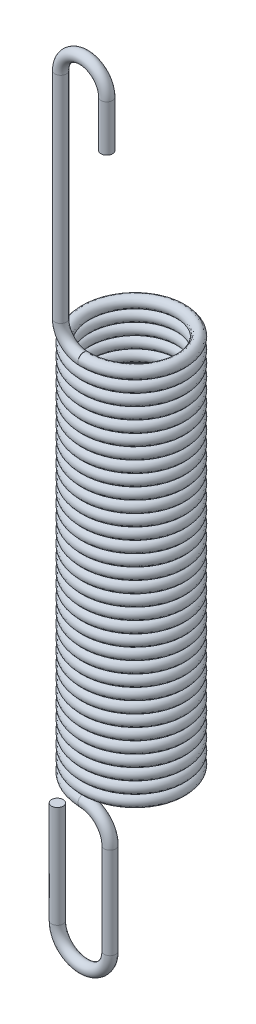
SolidWorks part; units mm, degrees
ref_plane "Front Plane" through (0, 0, 0) normal (0, 0, 1) x (1, 0, 0)
ref_plane "Top Plane" through (0, 0, 0) normal (0, 1, 0) x (1, 0, 0)
ref_plane "Right Plane" through (0, 0, 0) normal (1, 0, 0) x (0, 0, -1)
sketch "Sketch2" plane through (0, 0, 0) normal (0, 1, 0) x (1, 0, 0)
  circle A0 centre (0, 0) radius 19.6
curve "Helix/Spiral1" pitch 4.7664 height 157.29 turns 33
ref_plane "Plane1" through (0, 0, 19.6) normal (0, 0, 1) x (1, 0, 0)
sketch "Sketch3" plane through (0, 0, 19.6) normal (0, 0, 1) x (1, 0, 0)
  line L0 (10.85, -10.85) -> (10.85, -48.5)
  line L1 (-10.85, -48.5) -> (-10.85, -6.5)
  arc A0 (0, 0) -> (10.85, -10.85) centre (0, -10.85) cw
  arc A1 (10.85, -48.5) -> (-10.85, -48.5) centre (0, -48.5) cw
sketch "Sketch5" plane through (0, 0, 19.6) normal (0, 0, 1) x (1, 0, 0)
  line L0 (-9.5, 166.79) -> (-9.5, 255.29)
  line L1 (9.5, 255.29) -> (9.5, 236.29)
  arc A0 (0, 157.29) -> (-9.5, 166.79) centre (0, 166.79) cw
  arc A1 (-9.5, 255.29) -> (9.5, 255.29) centre (0, 255.29) cw
  spline S0 degree 3 poles (0, 0) (-2.088, 0.0808) (-6.2947, 0.2436) (-11.9376, 0.4869) (-16.3676, 0.7305) (-19.1242, 0.9739) (-19.9279, 1.2174) (-18.6961, 1.4609) (-15.5547, 1.7044) (-10.8245, 1.9479) (-4.9888, 2.1913) (1.3565, 2.4348) (7.5632, 2.6783) (12.9975, 2.9218) (17.1042, 3.1653) (19.4639, 3.4088) (19.8355, 3.6522) (18.1812, 3.8957) (14.6699, 4.1392) (9.6602, 4.3827) (3.6639, 4.6262) (-2.7067, 4.8697) (-8.8009, 5.1131) (-13.9961, 5.3566) (-17.7618, 5.6001) (-19.7133, 5.8436) (-19.6513, 6.0871) (-17.5822, 6.3306) (-13.7172, 6.574) (-8.4512, 6.8175) (-2.322, 7.061) (4.0444, 7.3045) (9.9977, 7.548) (14.9298, 7.7915) (18.337, 8.0349) (19.8713, 8.2784) (19.376, 8.5219) (16.9016, 8.7654) (12.7009, 9.0089) (7.203, 9.2524) (0.9693, 9.4958) (-5.3634, 9.7393) (-11.1482, 9.9828) (-15.7944, 10.2263) (-18.8273, 10.4698) (-19.9373, 10.7133) (-19.0109, 10.9567) (-16.1427, 11.2002) (-11.6258, 11.4437) (-5.9214, 11.6872) (0.3878, 11.9307) (6.6574, 12.1741) (12.2471, 12.4176) (16.5858, 12.6611) (19.2304, 12.9046) (19.9109, 13.1481) (18.5577, 13.3916) (15.3091, 13.635) (10.4968, 13.8785) (4.6123, 14.122) (-1.7432, 14.3655) (-7.9207, 14.609) (-13.2892, 14.8525) (-17.3003, 15.0959) (-19.5444, 15.3394) (-19.7922, 15.5829) (-18.0185, 15.8264) (-14.4045, 16.0699) (-9.3191, 16.3134) (-3.2819, 16.5568) (3.0905, 16.8003) (9.1472, 17.0438) (14.2697, 17.2873) (17.9346, 17.5308) (19.7678, 17.7743) (19.5819, 18.0177) (17.3959, 18.2612) (13.4331, 18.5047) (8.0983, 18.7482) (1.9363, 18.9917) (-4.4234, 19.2352) (-10.3314, 19.4786) (-15.1841, 19.7221) (-18.4859, 19.9656) (-19.8996, 20.2091) (-19.2808, 20.4526) (-16.6926, 20.6961) (-12.3995, 20.9395) (-6.8399, 21.183) (-0.5817, 21.4265) (5.7359, 21.67) (11.4677, 21.9135) (16.0281, 22.157) (18.9515, 22.4004) (19.9392, 22.6439) (18.8903, 22.8874) (15.912, 23.1309) (11.3085, 23.3744) (5.5499, 23.6178) (-0.7756, 23.8613) (-7.0218, 24.1048) (-12.5508, 24.3483) (-16.7979, 24.5918) (-19.3293, 24.8353) (-19.8864, 25.0787) (-18.4123, 25.3222) (-15.0577, 25.5657) (-10.165, 25.8092) (-4.2341, 26.0527) (2.1292, 26.2962) (8.2751, 26.5396) (13.5758, 26.7831) (17.4898, 27.0266) (19.6175, 27.2701) (19.7415, 27.5136) (17.849, 27.7571) (14.1335, 28.0005) (8.9745, 28.244) (2.8987, 28.4875) (-3.4731, 28.731) (-9.4901, 28.9745) (-14.5379, 29.218) (-18.1007, 29.4614) (-19.8148, 29.7049) (-19.5051, 29.9484) (-17.203, 30.1919) (-13.1439, 30.4354) (-7.7423, 30.6789) (-1.5499, 30.9223) (4.8008, 31.1658) (10.6611, 31.4093) (15.4326, 31.6528) (18.6278, 31.8963) (19.9203, 32.1398) (19.1783, 32.3832) (16.4773, 32.6267) (12.0934, 32.8702) (6.4743, 33.1137) (0.1939, 33.3572) (-6.1063, 33.6007) (-11.7828, 33.8441) (-16.2558, 34.0876) (-19.0685, 34.3311) (-19.9335, 34.5746) (-18.7626, 34.8181) (-15.6753, 35.0615) (-10.9869, 35.305) (-5.1763, 35.5485) (1.163, 35.792) (7.3835, 36.0355) (12.8498, 36.279) (17.0037, 36.5224) (19.4208, 36.7659) (19.8544, 37.0094) (18.26, 37.2529) (14.8006, 37.4964) (9.8294, 37.7399) (3.8543, 37.9833) (-2.5145, 38.2268) (-8.6264, 38.4703) (-13.8573, 38.7138) (-17.6728, 38.9573) (-19.6832, 39.2008) (-19.6832, 39.4442) (-17.6728, 39.6877) (-13.8573, 39.9312) (-8.6264, 40.1747) (-2.5145, 40.4182) (3.8543, 40.6617) (9.8294, 40.9051) (14.8006, 41.1486) (18.26, 41.3921) (19.8544, 41.6356) (19.4208, 41.8791) (17.0037, 42.1226) (12.8498, 42.366) (7.3835, 42.6095) (1.163, 42.853) (-5.1763, 43.0965) (-10.9869, 43.34) (-15.6753, 43.5835) (-18.7626, 43.8269) (-19.9335, 44.0704) (-19.0685, 44.3139) (-16.2558, 44.5574) (-11.7828, 44.8009) (-6.1063, 45.0443) (0.1939, 45.2878) (6.4743, 45.5313) (12.0934, 45.7748) (16.4773, 46.0183) (19.1783, 46.2618) (19.9203, 46.5052) (18.6278, 46.7487) (15.4326, 46.9922) (10.6611, 47.2357) (4.8008, 47.4792) (-1.5499, 47.7227) (-7.7423, 47.9661) (-13.1439, 48.2096) (-17.203, 48.4531) (-19.5051, 48.6966) (-19.8148, 48.9401) (-18.1007, 49.1836) (-14.5379, 49.427) (-9.4901, 49.6705) (-3.4731, 49.914) (2.8987, 50.1575) (8.9745, 50.401) (14.1335, 50.6445) (17.849, 50.8879) (19.7415, 51.1314) (19.6175, 51.3749) (17.4898, 51.6184) (13.5758, 51.8619) (8.2751, 52.1054) (2.1292, 52.3488) (-4.2341, 52.5923) (-10.165, 52.8358) (-15.0577, 53.0793) (-18.4123, 53.3228) (-19.8864, 53.5663) (-19.3293, 53.8097) (-16.7979, 54.0532) (-12.5508, 54.2967) (-7.0218, 54.5402) (-0.7756, 54.7837) (5.5499, 55.0272) (11.3085, 55.2706) (15.912, 55.5141) (18.8903, 55.7576) (19.9392, 56.0011) (18.9515, 56.2446) (16.0281, 56.488) (11.4677, 56.7315) (5.7359, 56.975) (-0.5817, 57.2185) (-6.8399, 57.462) (-12.3995, 57.7055) (-16.6926, 57.9489) (-19.2808, 58.1924) (-19.8996, 58.4359) (-18.4859, 58.6794) (-15.1841, 58.9229) (-10.3314, 59.1664) (-4.4234, 59.4098) (1.9363, 59.6533) (8.0983, 59.8968) (13.4331, 60.1403) (17.3959, 60.3838) (19.5819, 60.6273) (19.7678, 60.8707) (17.9346, 61.1142) (14.2697, 61.3577) (9.1472, 61.6012) (3.0905, 61.8447) (-3.2819, 62.0882) (-9.3191, 62.3316) (-14.4045, 62.5751) (-18.0185, 62.8186) (-19.7922, 63.0621) (-19.5444, 63.3056) (-17.3003, 63.5491) (-13.2892, 63.7925) (-7.9207, 64.036) (-1.7432, 64.2795) (4.6123, 64.523) (10.4968, 64.7665) (15.3091, 65.01) (18.5577, 65.2534) (19.9109, 65.4969) (19.2304, 65.7404) (16.5858, 65.9839) (12.2471, 66.2274) (6.6574, 66.4709) (0.3878, 66.7143) (-5.9214, 66.9578) (-11.6258, 67.2013) (-16.1427, 67.4448) (-19.0109, 67.6883) (-19.9373, 67.9317) (-18.8273, 68.1752) (-15.7944, 68.4187) (-11.1482, 68.6622) (-5.3634, 68.9057) (0.9693, 69.1492) (7.203, 69.3926) (12.7009, 69.6361) (16.9016, 69.8796) (19.376, 70.1231) (19.8713, 70.3666) (18.337, 70.6101) (14.9298, 70.8535) (9.9977, 71.097) (4.0444, 71.3405) (-2.322, 71.584) (-8.4512, 71.8275) (-13.7172, 72.071) (-17.5822, 72.3144) (-19.6513, 72.5579) (-19.7133, 72.8014) (-17.7618, 73.0449) (-13.9961, 73.2884) (-8.8009, 73.5319) (-2.7067, 73.7753) (3.6639, 74.0188) (9.6602, 74.2623) (14.6699, 74.5058) (18.1812, 74.7493) (19.8355, 74.9928) (19.4639, 75.2362) (17.1042, 75.4797) (12.9975, 75.7232) (7.5632, 75.9667) (1.3565, 76.2102) (-4.9888, 76.4537) (-10.8245, 76.6971) (-15.5547, 76.9406) (-18.6961, 77.1841) (-19.9279, 77.4276) (-19.1243, 77.6711) (-16.3673, 77.9146) (-11.9387, 78.158) (-4.4079, 78.4827) (4.4079, 78.8073) (11.9387, 79.132) (16.3673, 79.3754) (19.1243, 79.6189) (19.9279, 79.8624) (18.6961, 80.1059) (15.5547, 80.3494) (10.8245, 80.5929) (4.9888, 80.8363) (-1.3565, 81.0798) (-7.5632, 81.3233) (-12.9975, 81.5668) (-17.1042, 81.8103) (-19.4639, 82.0538) (-19.8355, 82.2972) (-18.1812, 82.5407) (-14.6699, 82.7842) (-9.6602, 83.0277) (-3.6639, 83.2712) (2.7067, 83.5147) (8.8009, 83.7581) (13.9961, 84.0016) (17.7618, 84.2451) (19.7133, 84.4886) (19.6513, 84.7321) (17.5822, 84.9756) (13.7172, 85.219) (8.4512, 85.4625) (2.322, 85.706) (-4.0444, 85.9495) (-9.9977, 86.193) (-14.9298, 86.4365) (-18.337, 86.6799) (-19.8713, 86.9234) (-19.376, 87.1669) (-16.9016, 87.4104) (-12.7009, 87.6539) (-7.203, 87.8974) (-0.9693, 88.1408) (5.3634, 88.3843) (11.1482, 88.6278) (15.7944, 88.8713) (18.8273, 89.1148) (19.9373, 89.3583) (19.0109, 89.6017) (16.1427, 89.8452) (11.6258, 90.0887) (5.9214, 90.3322) (-0.3878, 90.5757) (-6.6574, 90.8191) (-12.2471, 91.0626) (-16.5858, 91.3061) (-19.2304, 91.5496) (-19.9109, 91.7931) (-18.5577, 92.0366) (-15.3091, 92.28) (-10.4968, 92.5235) (-4.6123, 92.767) (1.7432, 93.0105) (7.9207, 93.254) (13.2892, 93.4975) (17.3003, 93.7409) (19.5444, 93.9844) (19.7922, 94.2279) (18.0185, 94.4714) (14.4045, 94.7149) (9.3191, 94.9584) (3.2819, 95.2018) (-3.0905, 95.4453) (-9.1472, 95.6888) (-14.2697, 95.9323) (-17.9346, 96.1758) (-19.7678, 96.4193) (-19.5819, 96.6627) (-17.3959, 96.9062) (-13.4331, 97.1497) (-8.0983, 97.3932) (-1.9363, 97.6367) (4.4234, 97.8802) (10.3314, 98.1236) (15.1841, 98.3671) (18.4859, 98.6106) (19.8996, 98.8541) (19.2808, 99.0976) (16.6926, 99.3411) (12.3995, 99.5845) (6.8399, 99.828) (0.5817, 100.0715) (-5.7359, 100.315) (-11.4677, 100.5585) (-16.0281, 100.802) (-18.9515, 101.0454) (-19.9392, 101.2889) (-18.8903, 101.5324) (-15.912, 101.7759) (-11.3085, 102.0194) (-5.5499, 102.2628) (0.7756, 102.5063) (7.0218, 102.7498) (12.5508, 102.9933) (16.7979, 103.2368) (19.3293, 103.4803) (19.8864, 103.7237) (18.4123, 103.9672) (15.0577, 104.2107) (10.165, 104.4542) (4.2341, 104.6977) (-2.1292, 104.9412) (-8.2751, 105.1846) (-13.5758, 105.4281) (-17.4898, 105.6716) (-19.6175, 105.9151) (-19.7415, 106.1586) (-17.849, 106.4021) (-14.1335, 106.6455) (-8.9745, 106.889) (-2.8987, 107.1325) (3.4731, 107.376) (9.4901, 107.6195) (14.5379, 107.863) (18.1007, 108.1064) (19.8148, 108.3499) (19.5051, 108.5934) (17.203, 108.8369) (13.1439, 109.0804) (7.7423, 109.3239) (1.5499, 109.5673) (-4.8008, 109.8108) (-10.6611, 110.0543) (-15.4326, 110.2978) (-18.6278, 110.5413) (-19.9203, 110.7848) (-19.1783, 111.0282) (-16.4773, 111.2717) (-12.0934, 111.5152) (-6.4743, 111.7587) (-0.1939, 112.0022) (6.1063, 112.2457) (11.7828, 112.4891) (16.2558, 112.7326) (19.0685, 112.9761) (19.9335, 113.2196) (18.7626, 113.4631) (15.6753, 113.7065) (10.9869, 113.95) (5.1763, 114.1935) (-1.163, 114.437) (-7.3835, 114.6805) (-12.8498, 114.924) (-17.0037, 115.1674) (-19.4208, 115.4109) (-19.8544, 115.6544) (-18.26, 115.8979) (-14.8006, 116.1414) (-9.8294, 116.3849) (-3.8543, 116.6283) (2.5145, 116.8718) (8.6264, 117.1153) (13.8573, 117.3588) (17.6728, 117.6023) (19.6832, 117.8458) (19.6832, 118.0892) (17.6728, 118.3327) (13.8573, 118.5762) (8.6264, 118.8197) (2.5145, 119.0632) (-3.8543, 119.3067) (-9.8294, 119.5501) (-14.8006, 119.7936) (-18.26, 120.0371) (-19.8544, 120.2806) (-19.4208, 120.5241) (-17.0037, 120.7676) (-12.8498, 121.011) (-7.3835, 121.2545) (-1.163, 121.498) (5.1763, 121.7415) (10.9869, 121.985) (15.6753, 122.2285) (18.7626, 122.4719) (19.9335, 122.7154) (19.0685, 122.9589) (16.2558, 123.2024) (11.7828, 123.4459) (6.1063, 123.6893) (-0.1939, 123.9328) (-6.4743, 124.1763) (-12.0934, 124.4198) (-16.4773, 124.6633) (-19.1783, 124.9068) (-19.9203, 125.1502) (-18.6278, 125.3937) (-15.4326, 125.6372) (-10.6611, 125.8807) (-4.8008, 126.1242) (1.5499, 126.3677) (7.7423, 126.6111) (13.1439, 126.8546) (17.203, 127.0981) (19.5051, 127.3416) (19.8148, 127.5851) (18.1007, 127.8286) (14.5379, 128.072) (9.4901, 128.3155) (3.4731, 128.559) (-2.8987, 128.8025) (-8.9745, 129.046) (-14.1335, 129.2895) (-17.849, 129.5329) (-19.7415, 129.7764) (-19.6175, 130.0199) (-17.4898, 130.2634) (-13.5758, 130.5069) (-8.2751, 130.7504) (-2.1292, 130.9938) (4.2341, 131.2373) (10.165, 131.4808) (15.0577, 131.7243) (18.4123, 131.9678) (19.8864, 132.2113) (19.3293, 132.4547) (16.7979, 132.6982) (12.5508, 132.9417) (7.0218, 133.1852) (0.7756, 133.4287) (-5.5499, 133.6722) (-11.3085, 133.9156) (-15.912, 134.1591) (-18.8903, 134.4026) (-19.9392, 134.6461) (-18.9515, 134.8896) (-16.0281, 135.133) (-11.4677, 135.3765) (-5.7359, 135.62) (0.5817, 135.8635) (6.8399, 136.107) (12.3995, 136.3505) (16.6926, 136.5939) (19.2808, 136.8374) (19.8996, 137.0809) (18.4859, 137.3244) (15.1841, 137.5679) (10.3314, 137.8114) (4.4234, 138.0548) (-1.9363, 138.2983) (-8.0983, 138.5418) (-13.4331, 138.7853) (-17.3959, 139.0288) (-19.5819, 139.2723) (-19.7678, 139.5157) (-17.9346, 139.7592) (-14.2697, 140.0027) (-9.1472, 140.2462) (-3.0905, 140.4897) (3.2819, 140.7332) (9.3191, 140.9766) (14.4045, 141.2201) (18.0185, 141.4636) (19.7922, 141.7071) (19.5444, 141.9506) (17.3003, 142.1941) (13.2892, 142.4375) (7.9207, 142.681) (1.7432, 142.9245) (-4.6123, 143.168) (-10.4968, 143.4115) (-15.3091, 143.655) (-18.5577, 143.8984) (-19.9109, 144.1419) (-19.2304, 144.3854) (-16.5858, 144.6289) (-12.2471, 144.8724) (-6.6574, 145.1159) (-0.3878, 145.3593) (5.9214, 145.6028) (11.6258, 145.8463) (16.1427, 146.0898) (19.0109, 146.3333) (19.9373, 146.5767) (18.8273, 146.8202) (15.7944, 147.0637) (11.1482, 147.3072) (5.3634, 147.5507) (-0.9693, 147.7942) (-7.203, 148.0376) (-12.7009, 148.2811) (-16.9016, 148.5246) (-19.376, 148.7681) (-19.8713, 149.0116) (-18.337, 149.2551) (-14.9298, 149.4985) (-9.9977, 149.742) (-4.0444, 149.9855) (2.322, 150.229) (8.4512, 150.4725) (13.7172, 150.716) (17.5822, 150.9594) (19.6513, 151.2029) (19.7133, 151.4464) (17.7618, 151.6899) (13.9961, 151.9334) (8.8009, 152.1769) (2.7067, 152.4203) (-3.6639, 152.6638) (-9.6602, 152.9073) (-14.6699, 153.1508) (-18.1812, 153.3943) (-19.8355, 153.6378) (-19.4639, 153.8812) (-17.1042, 154.1247) (-12.9975, 154.3682) (-7.5632, 154.6117) (-1.3565, 154.8552) (4.9888, 155.0987) (10.8245, 155.3421) (15.5547, 155.5856) (18.6961, 155.8291) (19.9279, 156.0726) (19.1242, 156.3161) (16.3676, 156.5595) (11.9376, 156.8031) (6.2947, 157.0464) (2.088, 157.2092) (0, 157.29) knots 0 0 0 0 0.001548 0.003096 0.004644 0.006192 0.00774 0.009288 0.010836 0.012384 0.013932 0.01548 0.017028 0.018576 0.020124 0.021672 0.02322 0.024768 0.026316 0.027864 0.029412 0.03096 0.032508 0.034056 0.035604 0.037152 0.0387 0.040248 0.041796 0.043344 0.044892 0.04644 0.047988 0.049536 0.051084 0.052632 0.05418 0.055728 0.057276 0.058824 0.060372 0.06192 0.063467 0.065015 0.066563 0.068111 0.069659 0.071207 0.072755 0.074303 0.075851 0.077399 0.078947 0.080495 0.082043 0.083591 0.085139 0.086687 0.088235 0.089783 0.091331 0.092879 0.094427 0.095975 0.097523 0.099071 0.100619 0.102167 0.103715 0.105263 0.106811 0.108359 0.109907 0.111455 0.113003 0.114551 0.116099 0.117647 0.119195 0.120743 0.122291 0.123839 0.125387 0.126935 0.128483 0.130031 0.131579 0.133127 0.134675 0.136223 0.137771 0.139319 0.140867 0.142415 0.143963 0.145511 0.147059 0.148607 0.150155 0.151703 0.153251 0.154799 0.156347 0.157895 0.159443 0.160991 0.162539 0.164087 0.165635 0.167183 0.168731 0.170279 0.171827 0.173375 0.174923 0.176471 0.178019 0.179567 0.181115 0.182663 0.184211 0.185759 0.187307 0.188854 0.190402 0.19195 0.193498 0.195046 0.196594 0.198142 0.19969 0.201238 0.202786 0.204334 0.205882 0.20743 0.208978 0.210526 0.212074 0.213622 0.21517 0.216718 0.218266 0.219814 0.221362 0.22291 0.224458 0.226006 0.227554 0.229102 0.23065 0.232198 0.233746 0.235294 0.236842 0.23839 0.239938 0.241486 0.243034 0.244582 0.24613 0.247678 0.249226 0.250774 0.252322 0.25387 0.255418 0.256966 0.258514 0.260062 0.26161 0.263158 0.264706 0.266254 0.267802 0.26935 0.270898 0.272446 0.273994 0.275542 0.27709 0.278638 0.280186 0.281734 0.283282 0.28483 0.286378 0.287926 0.289474 0.291022 0.29257 0.294118 0.295666 0.297214 0.298762 0.30031 0.301858 0.303406 0.304954 0.306502 0.30805 0.309598 0.311146 0.312693 0.314241 0.315789 0.317337 0.318885 0.320433 0.321981 0.323529 0.325077 0.326625 0.328173 0.329721 0.331269 0.332817 0.334365 0.335913 0.337461 0.339009 0.340557 0.342105 0.343653 0.345201 0.346749 0.348297 0.349845 0.351393 0.352941 0.354489 0.356037 0.357585 0.359133 0.360681 0.362229 0.363777 0.365325 0.366873 0.368421 0.369969 0.371517 0.373065 0.374613 0.376161 0.377709 0.379257 0.380805 0.382353 0.383901 0.385449 0.386997 0.388545 0.390093 0.391641 0.393189 0.394737 0.396285 0.397833 0.399381 0.400929 0.402477 0.404025 0.405573 0.407121 0.408669 0.410217 0.411765 0.413313 0.414861 0.416409 0.417957 0.419505 0.421053 0.422601 0.424149 0.425697 0.427245 0.428793 0.430341 0.431889 0.433437 0.434985 0.436533 0.43808 0.439628 0.441176 0.442724 0.444272 0.44582 0.447368 0.448916 0.450464 0.452012 0.45356 0.455108 0.456656 0.458204 0.459752 0.4613 0.462848 0.464396 0.465944 0.467492 0.46904 0.470588 0.472136 0.473684 0.475232 0.47678 0.478328 0.479876 0.481424 0.482972 0.48452 0.486068 0.487616 0.489164 0.490712 0.49226 0.493808 0.495356 0.496904 0.498452 0.501548 0.503096 0.504644 0.506192 0.50774 0.509288 0.510836 0.512384 0.513932 0.51548 0.517028 0.518576 0.520124 0.521672 0.52322 0.524768 0.526316 0.527864 0.529412 0.53096 0.532508 0.534056 0.535604 0.537152 0.5387 0.540248 0.541796 0.543344 0.544892 0.54644 0.547988 0.549536 0.551084 0.552632 0.55418 0.555728 0.557276 0.558824 0.560372 0.56192 0.563467 0.565015 0.566563 0.568111 0.569659 0.571207 0.572755 0.574303 0.575851 0.577399 0.578947 0.580495 0.582043 0.583591 0.585139 0.586687 0.588235 0.589783 0.591331 0.592879 0.594427 0.595975 0.597523 0.599071 0.600619 0.602167 0.603715 0.605263 0.606811 0.608359 0.609907 0.611455 0.613003 0.614551 0.616099 0.617647 0.619195 0.620743 0.622291 0.623839 0.625387 0.626935 0.628483 0.630031 0.631579 0.633127 0.634675 0.636223 0.637771 0.639319 0.640867 0.642415 0.643963 0.645511 0.647059 0.648607 0.650155 0.651703 0.653251 0.654799 0.656347 0.657895 0.659443 0.660991 0.662539 0.664087 0.665635 0.667183 0.668731 0.670279 0.671827 0.673375 0.674923 0.676471 0.678019 0.679567 0.681115 0.682663 0.684211 0.685759 0.687307 0.688854 0.690402 0.69195 0.693498 0.695046 0.696594 0.698142 0.69969 0.701238 0.702786 0.704334 0.705882 0.70743 0.708978 0.710526 0.712074 0.713622 0.71517 0.716718 0.718266 0.719814 0.721362 0.72291 0.724458 0.726006 0.727554 0.729102 0.73065 0.732198 0.733746 0.735294 0.736842 0.73839 0.739938 0.741486 0.743034 0.744582 0.74613 0.747678 0.749226 0.750774 0.752322 0.75387 0.755418 0.756966 0.758514 0.760062 0.76161 0.763158 0.764706 0.766254 0.767802 0.76935 0.770898 0.772446 0.773994 0.775542 0.77709 0.778638 0.780186 0.781734 0.783282 0.78483 0.786378 0.787926 0.789474 0.791022 0.79257 0.794118 0.795666 0.797214 0.798762 0.80031 0.801858 0.803406 0.804954 0.806502 0.80805 0.809598 0.811146 0.812693 0.814241 0.815789 0.817337 0.818885 0.820433 0.821981 0.823529 0.825077 0.826625 0.828173 0.829721 0.831269 0.832817 0.834365 0.835913 0.837461 0.839009 0.840557 0.842105 0.843653 0.845201 0.846749 0.848297 0.849845 0.851393 0.852941 0.854489 0.856037 0.857585 0.859133 0.860681 0.862229 0.863777 0.865325 0.866873 0.868421 0.869969 0.871517 0.873065 0.874613 0.876161 0.877709 0.879257 0.880805 0.882353 0.883901 0.885449 0.886997 0.888545 0.890093 0.891641 0.893189 0.894737 0.896285 0.897833 0.899381 0.900929 0.902477 0.904025 0.905573 0.907121 0.908669 0.910217 0.911765 0.913313 0.914861 0.916409 0.917957 0.919505 0.921053 0.922601 0.924149 0.925697 0.927245 0.928793 0.930341 0.931889 0.933437 0.934985 0.936533 0.93808 0.939628 0.941176 0.942724 0.944272 0.94582 0.947368 0.948916 0.950464 0.952012 0.95356 0.955108 0.956656 0.958204 0.959752 0.9613 0.962848 0.964396 0.965944 0.967492 0.96904 0.970588 0.972136 0.973684 0.975232 0.97678 0.978328 0.979876 0.981424 0.982972 0.98452 0.986068 0.987616 0.989164 0.990712 0.99226 0.993808 0.995356 0.996904 0.998452 1 1 1 1 construction
sweep "Sweep4" add path "Sketch3" circular profile diameter 4.75 parameters "D3"=4.75
sweep "Sweep5" add path "Sketch5" circular profile diameter 4.75 parameters "D3"=4.75
sweep "Sweep6" add path "Helix/Spiral1" circular profile diameter 4.75 parameters "D3"=4.75
